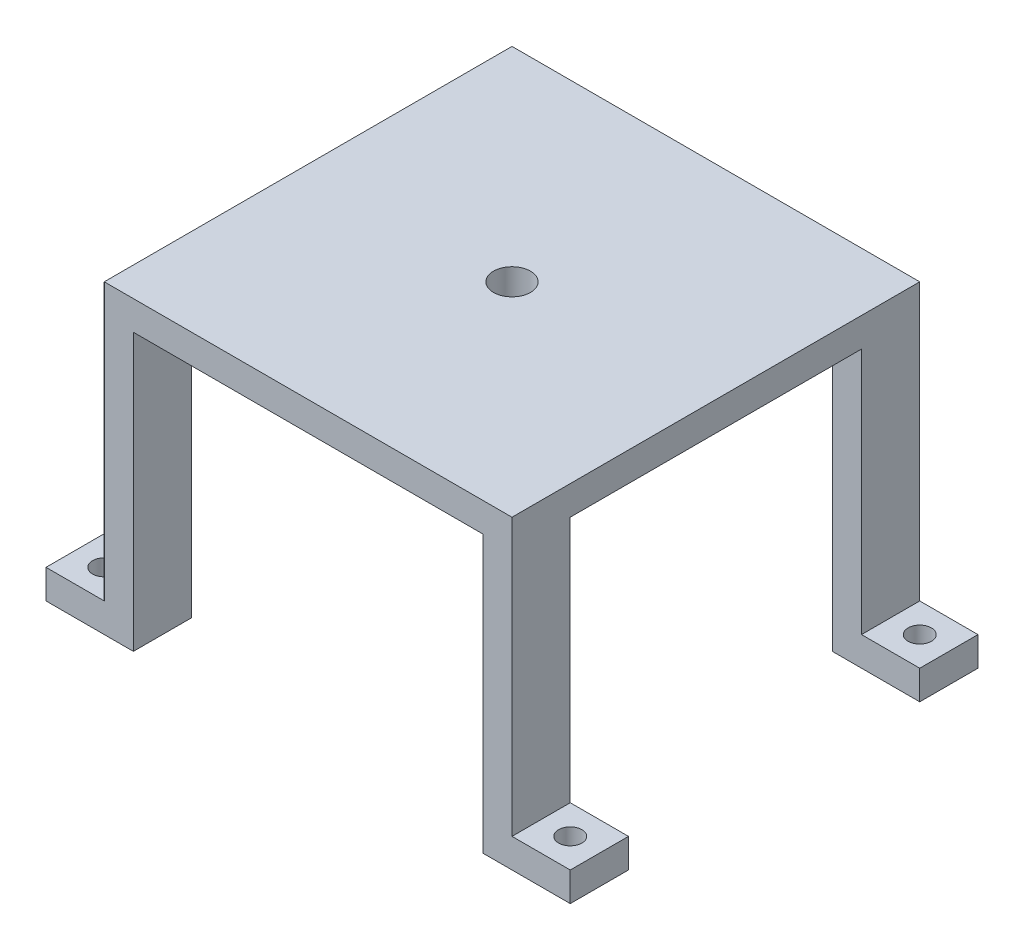
SolidWorks part; units mm, degrees
ref_plane "Front Plane" through (0, 0, 0) normal (0, 0, 1) x (1, 0, 0)
ref_plane "Top Plane" through (0, 0, 0) normal (0, 1, 0) x (1, 0, 0)
ref_plane "Right Plane" through (0, 0, 0) normal (1, 0, 0) x (0, 0, -1)
sketch "Sketch1" plane through (0, 0, 0) normal (0, 1, 0) x (1, 0, 0)
  line L0 (0, 0) -> (0, 22.7729) construction
  line L1 (0, 0) -> (43.3552, 0) construction
  line L2 (-35, 35) -> (35, 35)
  line L3 (35, 35) -> (35, -35)
  line L4 (-35, 35) -> (-35, -35)
  line L5 (-35, -35) -> (35, -35)
  point P9 (0, 35)
  point P10 (35, 0)
  point P11 (-35, 0)
  dimension "D1" = 35
  dimension "D2" = 35
extrude "Boss-Extrude1" add sketch "Sketch1" along normal blind 52.45
sketch "Sketch2" plane through (0, 0, 35) normal (0, 0, 1) x (1, 0, 0)
  line L0 (-35, 0) -> (-30, 0)
  line L1 (-35, 0) -> (35, 0) construction
  line L2 (-35, 0) -> (-35, 52.45)
  line L3 (-35, 52.45) -> (35, 52.45)
  line L4 (35, 52.45) -> (35, 0)
  line L5 (35, 0) -> (30, 0)
  line L6 (30, 0) -> (30, 47.45)
  line L7 (30, 47.45) -> (-30, 47.45)
  line L8 (-30, 47.45) -> (-30, 0)
  line L9 (-30, 0) -> (30, 0)
  point P5 (0, 0)
  point P15 (0, 0)
  point P16 (0, 0)
  point P17 (0, 0)
  point P18 (0, 0)
  dimension "D1" = 5
  dimension "D2" = 5
  dimension "D3" = 5
extrude "Cut-Extrude2" cut sketch "Sketch2" against normal blind 70 and the other way through all contours L6 L7 L8
ref_plane "Plane1" through (0, 0, 0) normal (0, 1, 0) x (1, 0, 0)
sketch "Sketch3" plane through (0, 0, 0) normal (0, 1, 0) x (1, 0, 0)
  line L0 (0, 0) -> (0, -37.5748) construction
  line L1 (35, -35) -> (45, -35)
  line L2 (35, -35) -> (35, -25)
  line L3 (35, -25) -> (45, -25)
  line L4 (45, -35) -> (45, -25)
  line L5 (0, 0) -> (50.9293, 0) construction
  line L6 (35, 35) -> (35, 25)
  line L7 (35, 35) -> (45, 35)
  line L8 (45, 35) -> (45, 25)
  line L9 (35, 25) -> (45, 25)
  line L10 (-45, -35) -> (-45, -25)
  line L11 (-35, -35) -> (-45, -35)
  line L12 (-35, -35) -> (-35, -25)
  line L13 (-35, -25) -> (-45, -25)
  line L14 (-35, 25) -> (-45, 25)
  line L15 (-45, 35) -> (-45, 25)
  line L16 (-35, 35) -> (-45, 35)
  line L17 (-35, 35) -> (-35, 25)
  line L18 (45, -30) -> (35, -30) construction
  circle A0 centre (40, -30) radius 2
  circle A1 centre (40, 30) radius 2
  circle A2 centre (-40, -30) radius 2
  circle A3 centre (-40, 30) radius 2
  dimension "D3" = 4
  dimension "D1" = 10
  dimension "D2" = 10
extrude "Boss-Extrude2" add sketch "Sketch3" along normal blind 5
sketch "Sketch4" plane through (0, 52.45, 0) normal (0, 1, 0) x (1, 0, 0)
  circle A0 centre (0, 0) radius 3.175
  dimension "D1" = 6.35
extrude "Cut-Extrude3" cut sketch "Sketch4" against normal blind 5
sketch "Sketch5" plane through (35, 0, 0) normal (1, 0, 0) x (0, 0, -1)
  line L0 (0, 0) -> (0, 19.4605) construction
  line L1 (38.5, 0) -> (-38.5, 0) construction
  line L2 (-25, 0) -> (25, 0)
  line L3 (-25, 0) -> (-25, 47.45)
  line L4 (-25, 47.45) -> (25, 47.45)
  line L5 (25, 0) -> (25, 47.45)
  line L6 (-35, 52.45) -> (-35, 5) construction
  line L7 (35, 52.45) -> (35, 5) construction
  line L8 (-35, 52.45) -> (35, 52.45) construction
  dimension "D1" = 10
  dimension "D2" = 10
  dimension "D3" = 5
extrude "Cut-Extrude4" cut sketch "Sketch5" against normal blind 80
sketch "Sketch6" plane through (0, 52.45, 0) normal (0, 1, 0) x (1, 0, 0)
  circle A0 centre (0, 0) radius 31 construction
  dimension "D1" = 62
